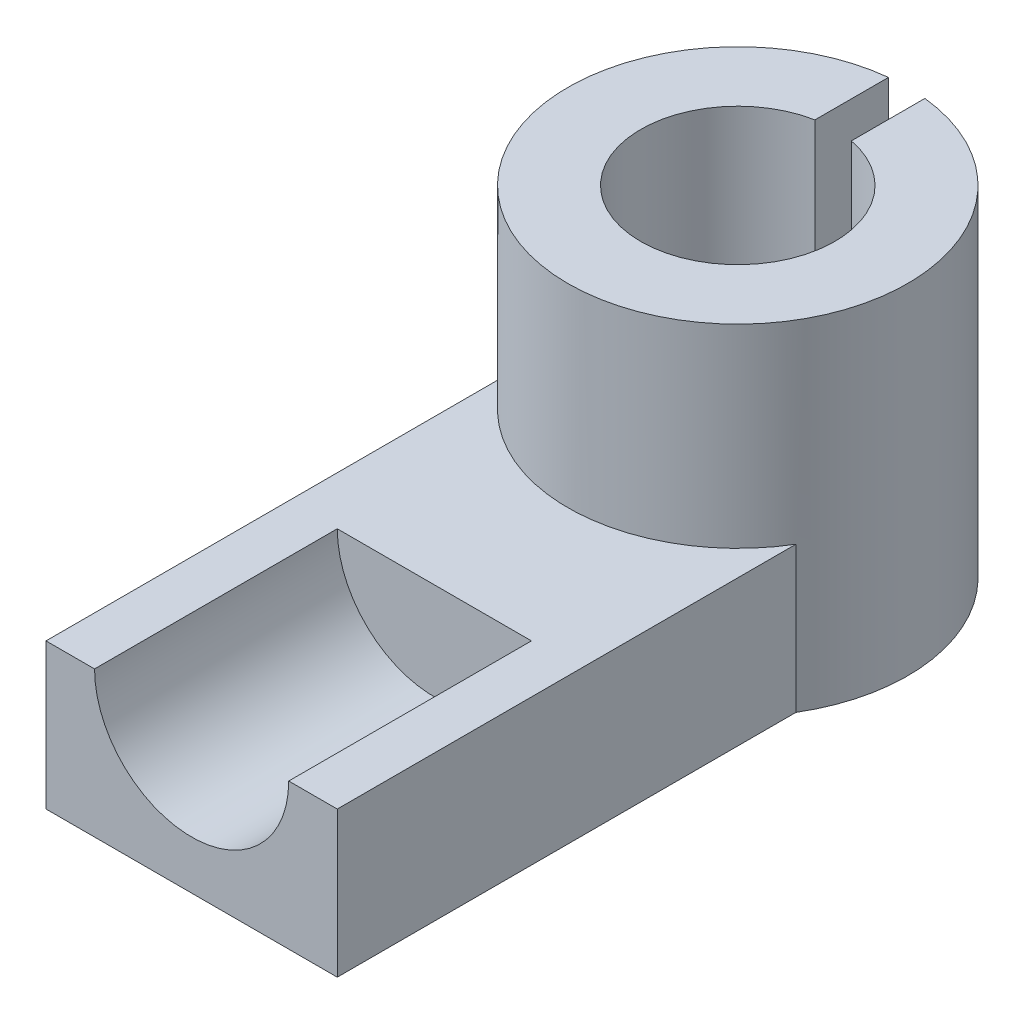
SolidWorks part; units mm, degrees
ref_plane "Front Plane" through (0, 0, 0) normal (0, 0, 1) x (1, 0, 0)
ref_plane "Top Plane" through (0, 0, 0) normal (0, 1, 0) x (1, 0, 0)
ref_plane "Right Plane" through (0, 0, 0) normal (1, 0, 0) x (0, 0, -1)
sketch "Sketch1" plane through (0, 0, 0) normal (0, 1, 0) x (1, 0, 0)
  circle A0 centre (0, 0) radius 16
  circle A1 centre (0, 0) radius 28
  dimension "D1" = 32
  dimension "D2" = 56
extrude "Boss-Extrude1" add sketch "Sketch1" along normal blind 56
sketch "Sketch2" plane through (0, 56, 0) normal (0, 1, 0) x (1, 0, 0)
  line L1 (-3, 2.7192) -> (3, 2.7192)
  line L2 (-3, 2.7192) -> (-3, 29.2808)
  line L3 (-3, 29.2808) -> (3, 29.2808)
  line L4 (3, 2.7192) -> (3, 29.2808)
  line L5 (-3, 2.7192) -> (3, 29.2808) construction
  line L6 (-3, 29.2808) -> (3, 2.7192) construction
  circle A0 centre (0, 0) radius 16 construction
  point P0 (0, 16)
  dimension "D1" = 6
  dimension "D2" = 26.5615
extrude "Cut-Extrude1" cut sketch "Sketch2" against normal through all
sketch "Sketch3" plane through (0, 0, 0) normal (0, -1, 0) x (1, 0, 0)
  line L0 (0, -6.7072) -> (0, 77.9277) construction
  line L1 (-24, 90) -> (24, 90)
  line L2 (-24, 90) -> (-24, 14.4222)
  line L4 (24, 90) -> (24, 14.4222)
  line L7 (3, -15.7162) -> (3, -27.8388)
  line L8 (-3, -27.8388) -> (-3, -15.7162)
  arc A0 (3, -27.8388) -> (-3, -27.8388) centre (0, 0) ccw construction
  arc A3 (3, -15.7162) -> (-3, -15.7162) centre (0, 0) ccw
  arc A4 (3, -27.8388) -> (-3, -27.8388) centre (0, 0) ccw
  arc A6 (24, 14.4222) -> (-24, 14.4222) centre (0, 0) ccw
  point P7 (24, 14.4222)
  point P11 (-24, 14.4222)
  dimension "D1" = 48
  dimension "D2" = 90
  dimension "D3" = 0
extrude "Boss-Extrude2" add sketch "Sketch3" against normal blind 24 contours L4 A6 L2 L1
sketch "Sketch4" plane through (0, 0, 90) normal (0, 0, 1) x (1, 0, 0)
  line L0 (-24, 24) -> (24, 24) construction
  circle A0 centre (0, 24) radius 16
  dimension "D1" = 32
extrude "Cut-Extrude2" cut sketch "Sketch4" against normal blind 40
